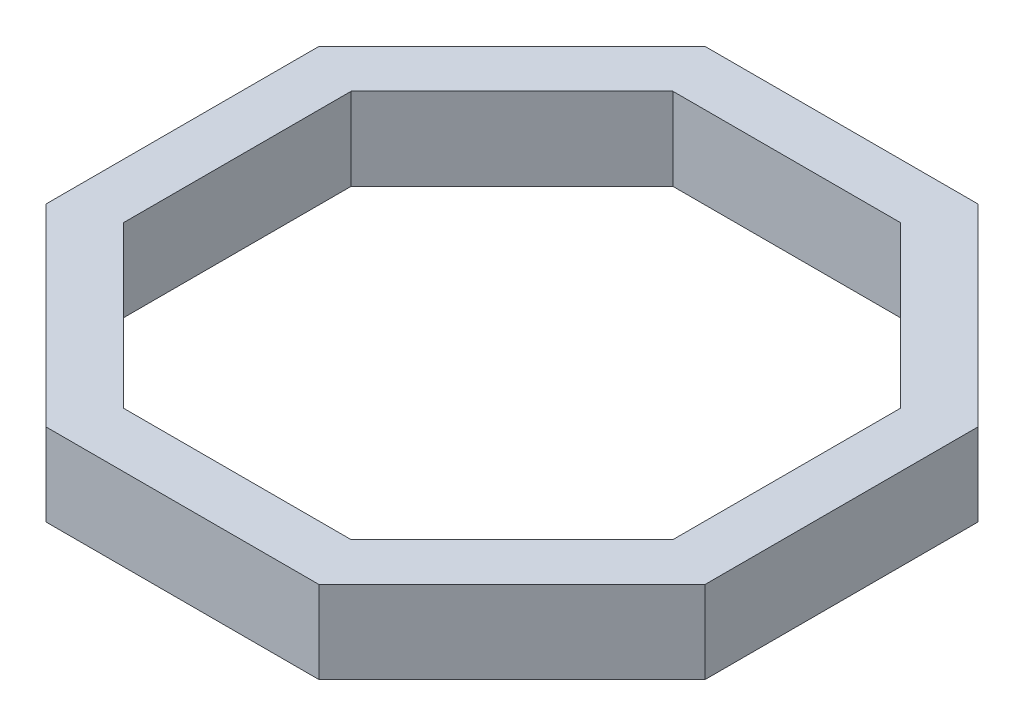
SolidWorks part; units mm, degrees
ref_plane "Plano frontal" through (0, 0, 0) normal (0, 0, 1) x (1, 0, 0)
ref_plane "Plano superior" through (0, 0, 0) normal (0, 1, 0) x (1, 0, 0)
ref_plane "Plano direito" through (0, 0, 0) normal (1, 0, 0) x (0, 0, -1)
sketch "Esboço1" plane through (0, 0, 0) normal (0, 1, 0) x (1, 0, 0)
  line L1 (120, 49.7056) -> (49.7056, 120)
  line L2 (49.7056, 120) -> (-49.7056, 120)
  line L3 (-49.7056, 120) -> (-120, 49.7056)
  line L4 (-120, 49.7056) -> (-120, -49.7056)
  line L5 (-120, -49.7056) -> (-49.7056, -120)
  line L6 (-49.7056, -120) -> (49.7056, -120)
  line L7 (49.7056, -120) -> (120, -49.7056)
  line L8 (120, -49.7056) -> (120, 49.7056)
  circle A0 centre (0, 0) radius 120 construction
extrude "Ressalto-extrusão2" add sketch "Esboço1" along normal blind 30
sketch "Esboço3" plane through (0, 30, 0) normal (0, 1, 0) x (1, 0, 0)
  line L1 (100, 41.4214) -> (41.4214, 100)
  line L2 (41.4214, 100) -> (-41.4214, 100)
  line L3 (-41.4214, 100) -> (-100, 41.4214)
  line L4 (-100, 41.4214) -> (-100, -41.4214)
  line L5 (-100, -41.4214) -> (-41.4214, -100)
  line L6 (-41.4214, -100) -> (41.4214, -100)
  line L7 (41.4214, -100) -> (100, -41.4214)
  line L8 (100, -41.4214) -> (100, 41.4214)
  circle A0 centre (0, 0) radius 100 construction
extrude "Corte-extrusão2" cut sketch "Esboço3" against normal blind 30
